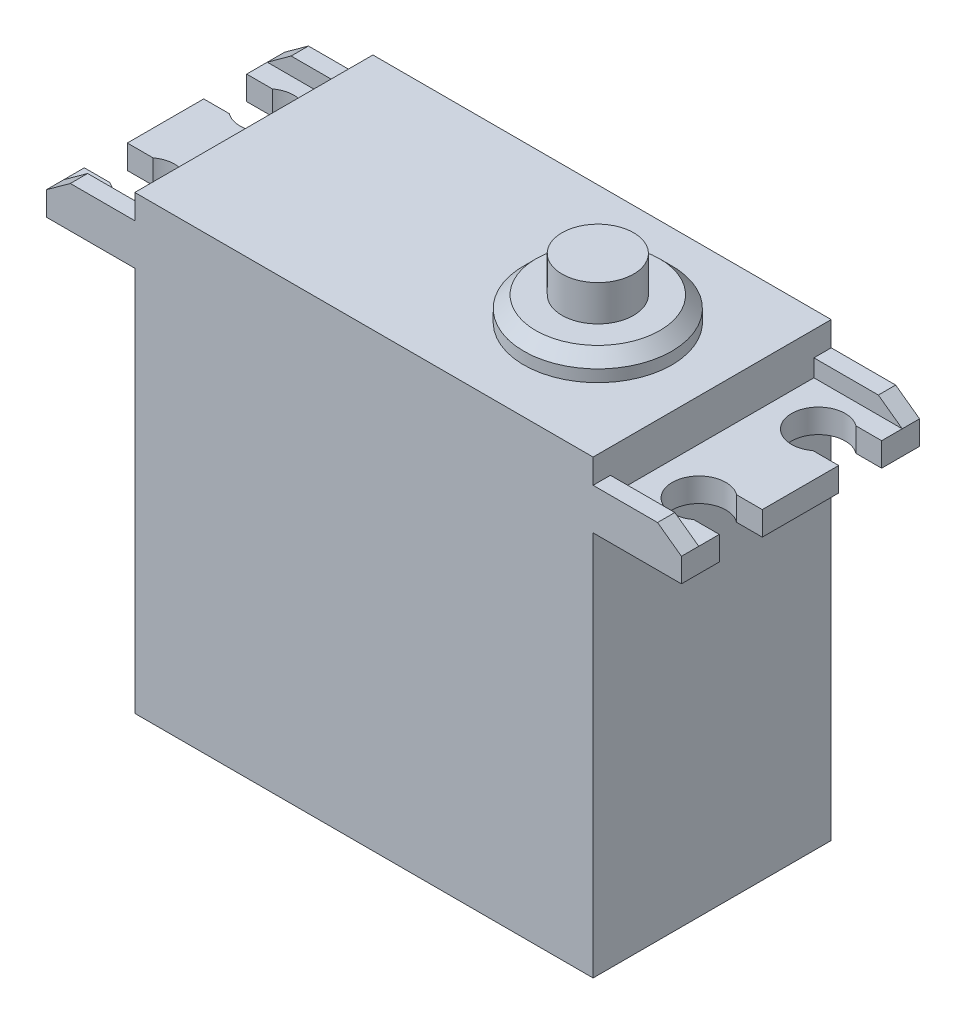
SolidWorks part; units mm, degrees
ref_plane "前基準面" through (0, 0, 0) normal (0, 0, 1) x (1, 0, 0)
ref_plane "上基準面" through (0, 0, 0) normal (0, 1, 0) x (1, 0, 0)
ref_plane "右基準面" through (0, 0, 0) normal (1, 0, 0) x (0, 0, -1)
sketch "草圖1" plane through (0, 0, 0) normal (0, 0, 1) x (1, 0, 0)
  line L0 (-14.4702, -11.8252) -> (-14.4702, -44.1252)
  line L1 (-14.4702, -44.1252) -> (23.9298, -44.1252)
  line L2 (23.9298, -44.1252) -> (23.9298, -11.8252)
  line L3 (23.9298, -11.8252) -> (31.3298, -11.8252)
  line L4 (31.3298, -11.8252) -> (31.3298, -9.8252)
  line L5 (31.3298, -9.8252) -> (23.9298, -9.8252)
  line L6 (23.9298, -9.8252) -> (23.9298, -6.3252)
  line L7 (23.9298, -6.3252) -> (-14.4702, -6.3252)
  line L8 (-14.4702, -6.3252) -> (-14.4702, -9.8252)
  line L9 (-14.4702, -9.8252) -> (-21.8702, -9.8252)
  line L10 (-21.8702, -9.8252) -> (-21.8702, -11.8252)
  line L11 (-21.8702, -11.8252) -> (-14.4702, -11.8252)
  dimension "D1" = 38.4
  dimension "D2" = 2
  dimension "D3" = 2
  dimension "D4" = 37.8
  dimension "D5" = 32.3
  dimension "D6" = 32.3
  dimension "D7" = 7.4
  dimension "D8" = 7.4
  dimension "D9" = 7.4
  dimension "D10" = 38.4
extrude "填料-伸長1" add sketch "草圖1" along normal blind 19.95
sketch "草圖2" plane through (0, -9.8252, 0) normal (0, 1, 0) x (1, 0, 0)
  line L0 (31.3298, -19.95) -> (31.3298, 0) construction
  line L1 (23.9298, 0) -> (31.3298, 0)
  line L2 (23.9298, 0) -> (23.9298, -1.45)
  line L3 (23.9298, -1.45) -> (31.3298, -1.45)
  line L4 (31.3298, 0) -> (31.3298, -1.45)
  line L5 (23.9298, -19.95) -> (23.9298, 0) construction
  line L6 (31.3298, -19.95) -> (23.9298, -19.95)
  line L7 (31.3298, -19.95) -> (31.3298, -18.5)
  line L8 (31.3298, -18.5) -> (23.9298, -18.5)
  line L9 (23.9298, -19.95) -> (23.9298, -18.5)
  line L10 (-14.4702, -19.95) -> (-14.4702, 0) construction
  line L11 (-21.8702, 0) -> (-14.4702, 0)
  line L12 (-21.8702, 0) -> (-21.8702, -1.45)
  line L13 (-21.8702, -1.45) -> (-14.4702, -1.45)
  line L14 (-14.4702, 0) -> (-14.4702, -1.45)
  line L15 (-14.4702, -19.95) -> (-14.4702, 0) construction
  line L16 (-21.8702, -19.95) -> (-14.4702, -19.95)
  line L17 (-21.8702, -19.95) -> (-21.8702, -18.5)
  line L18 (-21.8702, -18.5) -> (-14.4702, -18.5)
  line L19 (-14.4702, -19.95) -> (-14.4702, -18.5)
  dimension "D1" = 1.45
  dimension "D2" = 1.45
  dimension "D3" = 1.45
  dimension "D4" = 1.45
extrude "填料-伸長2" add sketch "草圖2" along normal blind 1.45
chamfer "導角1" distance 1.45 distance2 2 1 edges at (31.3298, -8.3752, 19.225)
chamfer "導角3" distance 1.45 distance2 2 1 edges at (31.3298, -8.3752, 0.725)
chamfer "導角4" distance 1.45 distance2 2 1 edges at (-21.8702, -8.3752, 19.225)
chamfer "導角5" distance 1.45 distance2 2 1 edges at (-21.8702, -8.3752, 0.725)
sketch "草圖3" plane through (0, -9.8252, 0) normal (0, 1, 0) x (1, 0, 0)
  line L0 (-19.8702, -19.95) -> (-14.4702, -19.95) construction
  line L1 (23.9298, -19.95) -> (29.3298, -19.95) construction
  line L2 (-21.8702, -18.5) -> (-21.8702, -1.45) construction
  circle A0 centre (-18.3702, -4.975) radius 2.25
  circle A1 centre (-18.3702, -14.975) radius 2.25
  circle A2 centre (27.8298, -14.975) radius 2.25
  circle A3 centre (27.8298, -4.975) radius 2.25
  dimension "D2" = 4.5
  dimension "D3" = 4.5
  dimension "D6" = 4.5
  dimension "D7" = 4.5
  dimension "D1" = 10
  dimension "D4" = 4.975
  dimension "D5" = 4.975
  dimension "D8" = 10
  dimension "D9" = 46.2
  dimension "D10" = 46.2
  dimension "D11" = 0
  dimension "D12" = 3.5
extrude "除料-伸長1" cut sketch "草圖3" against normal blind 2
sketch "草圖4" plane through (0, -9.8252, 0) normal (0, 1, 0) x (1, 0, 0)
  line L0 (-21.8702, -18.5) -> (-21.8702, -1.45) construction
  line L1 (-21.8702, -13.175) -> (-19.2681, -13.175)
  line L2 (-21.8702, -13.175) -> (-21.8702, -16.775)
  line L3 (-21.8702, -16.775) -> (-19.2681, -16.775)
  line L4 (-19.2681, -13.175) -> (-19.2681, -16.775)
  line L5 (-19.8702, -19.95) -> (-14.4702, -19.95) construction
  line L6 (31.3298, -18.5) -> (31.3298, -1.45) construction
  line L7 (-21.8702, -3.175) -> (-19.2681, -3.175)
  line L8 (-21.8702, -3.175) -> (-21.8702, -6.775)
  line L9 (-21.8702, -6.775) -> (-19.2681, -6.775)
  line L10 (-19.2681, -3.175) -> (-19.2681, -6.775)
  line L11 (31.3298, -13.175) -> (28.4776, -13.175)
  line L12 (31.3298, -13.175) -> (31.3298, -16.775)
  line L13 (31.3298, -16.775) -> (28.4776, -16.775)
  line L14 (28.4776, -13.175) -> (28.4776, -16.775)
  line L15 (-14.4702, 0) -> (-19.8702, 0) construction
  line L17 (31.3298, -3.175) -> (28.4776, -3.175)
  line L18 (31.3298, -3.175) -> (31.3298, -6.775)
  line L19 (31.3298, -6.775) -> (28.4776, -6.775)
  line L20 (28.4776, -3.175) -> (28.4776, -6.775)
  dimension "D1" = 3.6
  dimension "D2" = 3.175
  dimension "D3" = 3.6
  dimension "D4" = 3.175
extrude "除料-伸長2" cut sketch "草圖4" against normal blind 2
sketch "草圖5" plane through (0, -6.3252, 0) normal (0, 1, 0) x (1, 0, 0)
  line L0 (23.9298, -19.95) -> (-14.4702, -19.95) construction
  circle A0 centre (14.3498, -9.975) radius 6.2
  arc A1 (29.1798, -13.175) -> (29.1798, -16.775) centre (27.8298, -14.975) ccw construction
  arc A2 (-19.7202, -16.775) -> (-19.7202, -13.175) centre (-18.3702, -14.975) ccw construction
  dimension "D4" = 12.4
  dimension "D1" = 13.48
  dimension "D2" = 9.975
  dimension "D3" = 32.72
extrude "填料-伸長3" add sketch "草圖5" along normal blind 2
chamfer "導角6" distance 1 angle 45 1 edges at (8.1498, -4.3252, 9.975)
sketch "草圖6" plane through (0, -4.3252, 0) normal (0, 1, 0) x (1, 0, 0)
  circle A0 centre (14.3498, -9.975) radius 3
  circle A1 centre (14.3498, -9.975) radius 5.2 construction
  dimension "D1" = 6
  dimension "D2" = 0
extrude "填料-伸長4" add sketch "草圖6" along normal blind 3
